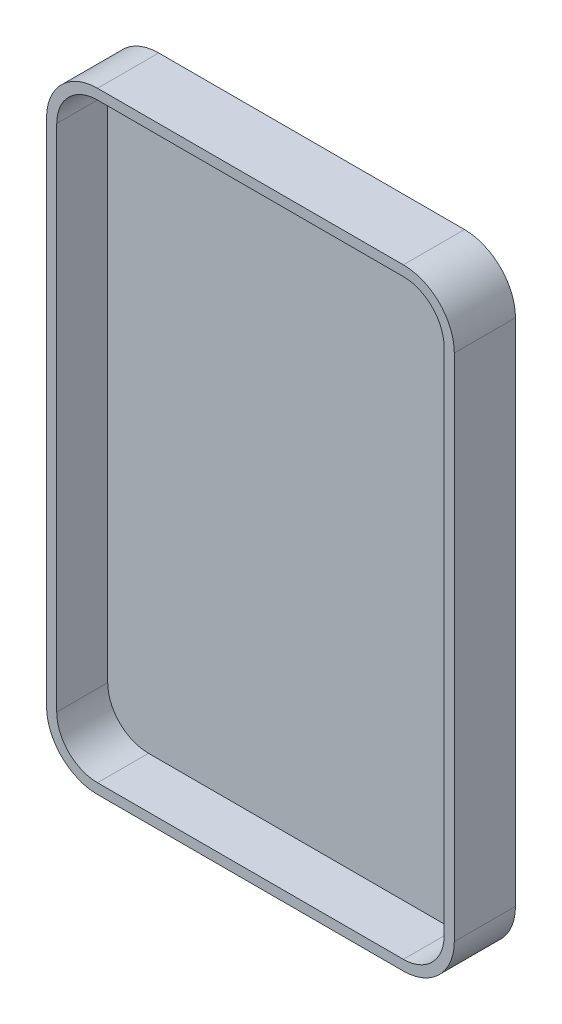
SolidWorks part; units mm, degrees
ref_plane "Plan de face" through (0, 0, 0) normal (0, 0, 1) x (1, 0, 0)
ref_plane "Plan de dessus" through (0, 0, 0) normal (0, 1, 0) x (1, 0, 0)
ref_plane "Plan de droite" through (0, 0, 0) normal (1, 0, 0) x (0, 0, -1)
sketch "Esquisse1" plane through (0, 0, 0) normal (0, 0, 1) x (1, 0, 0)
  line L1 (0, 0) -> (-80, 0)
  line L2 (0, 0) -> (0, 120)
  line L3 (0, 120) -> (-80, 120)
  line L4 (-80, 0) -> (-80, 120)
  circle A0 centre (-70, 110) radius 10
  circle A1 centre (-10, 110) radius 10
  circle A2 centre (-70, 10) radius 10
  circle A3 centre (-10, 10) radius 10
  dimension "D3" = 20
  dimension "D4" = 20
  dimension "D5" = 20
  dimension "D1" = 120
  dimension "D2" = 80
extrude "Boss.-Extru.3" add sketch "Esquisse1" along normal blind 2 contours A3 L2 A1 L3 A0 L4 A2 L1 | A0 | A1 | A3 | A2
sketch "Esquisse3" plane through (0, 0, 2) normal (0, 0, 1) x (1, 0, 0)
  line L0 (-10, 120) -> (-70, 120) construction
  line L1 (-2, 2) -> (-78, 2)
  line L2 (-2, 2) -> (-2, 118)
  line L3 (-2, 118) -> (-78, 118)
  line L4 (-78, 2) -> (-78, 118)
  line L5 (0, 10) -> (0, 110) construction
  line L6 (-10, 0) -> (-70, 0) construction
  line L7 (-80, 10) -> (-80, 110) construction
  circle A0 centre (-70, 110) radius 10
  circle A1 centre (-10, 110) radius 10
  circle A2 centre (-10, 10) radius 10
  circle A3 centre (-70, 10) radius 10
  circle A4 centre (-10, 110) radius 8
  circle A5 centre (-70, 110) radius 8
  circle A6 centre (-70, 10) radius 8
  circle A7 centre (-10, 10) radius 8
  line M6 (-70, 0) -> (-10, 0)
  arc M7 (-10, 0) -> (0, 10) centre (-10, 10) ccw
  line M8 (0, 10) -> (0, 110)
  arc M9 (0, 110) -> (-10, 120) centre (-10, 110) ccw
  line M10 (-10, 120) -> (-70, 120)
  arc M11 (-70, 120) -> (-80, 110) centre (-70, 110) ccw
  line M12 (-80, 110) -> (-80, 10)
  arc M13 (-80, 10) -> (-70, 0) centre (-70, 10) ccw
  dimension "D1" = 2
  dimension "D2" = 2
  dimension "D3" = 2
  dimension "D4" = 2
extrude "Boss.-Extru.4" add sketch "Esquisse3" along normal blind 10 contours L4 A3 M13 | A6 L4 L1 M13 | A3 L1 M13 | A3 A2 L1 M6 | A3 L4 A0 M12 | A0 L4 M11 | A5 L3 L4 M11 | L3 A0 M11 | A1 A0 L3 M10 | A1 L3 M9 | A4 L2 L3 M9 | L2 A1 M9 | A2 A1 L2 M8 | A2 L2 M7 | A7 L1 L2 M7 | L1 A2 M7
